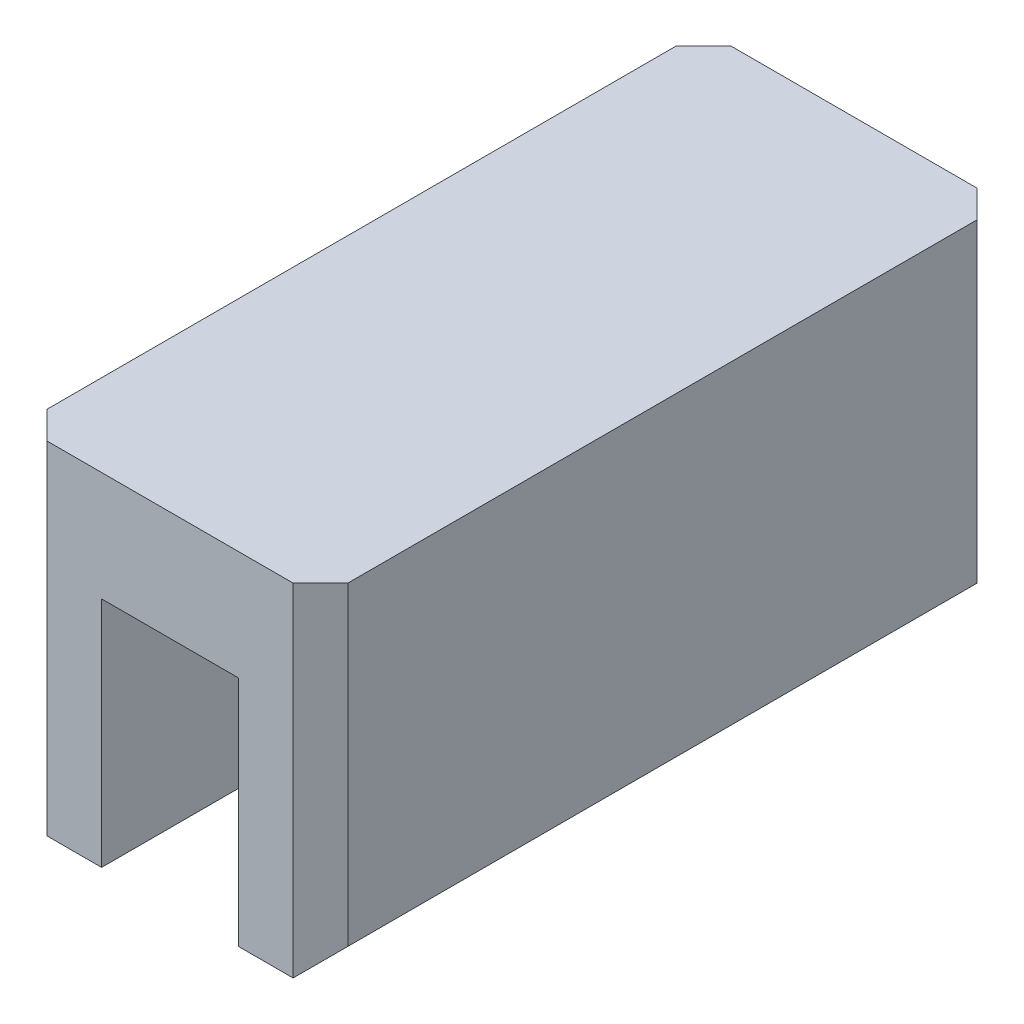
SolidWorks part; units mm, degrees
material "ABS"
ref_plane "Piano frontale" through (0, 0, 0) normal (0, 0, 1) x (1, 0, 0)
ref_plane "Piano superiore" through (0, 0, 0) normal (0, 1, 0) x (1, 0, 0)
ref_plane "Piano destro" through (0, 0, 0) normal (1, 0, 0) x (0, 0, -1)
sketch "Schizzo1" plane through (0, 0, 0) normal (0, 0, 1) x (1, 0, 0)
  line L0 (5, 0) -> (-5, 0)
  line L1 (-5, 0) -> (-5, -17)
  line L2 (-5, -17) -> (-11, -17)
  line L3 (-11, -17) -> (-11, 8)
  line L4 (-11, 8) -> (11, 8)
  line L5 (11, 8) -> (11, -17)
  line L6 (11, -17) -> (5, -17)
  line L7 (5, -17) -> (5, 0)
  dimension "D1" = 10
  dimension "D2" = 8
  dimension "D3" = 25
  dimension "D4" = 6
extrude "Estrusione-Estrusione1" add sketch "Schizzo1" along normal blind 50
chamfer "Smusso1" distance 2 angle 45 6 edges at (-11, -4.5, 0) (-11, -17, 25) (-11, -4.5, 50) (11, -4.5, 0) (11, -17, 25) (11, -4.5, 50)
